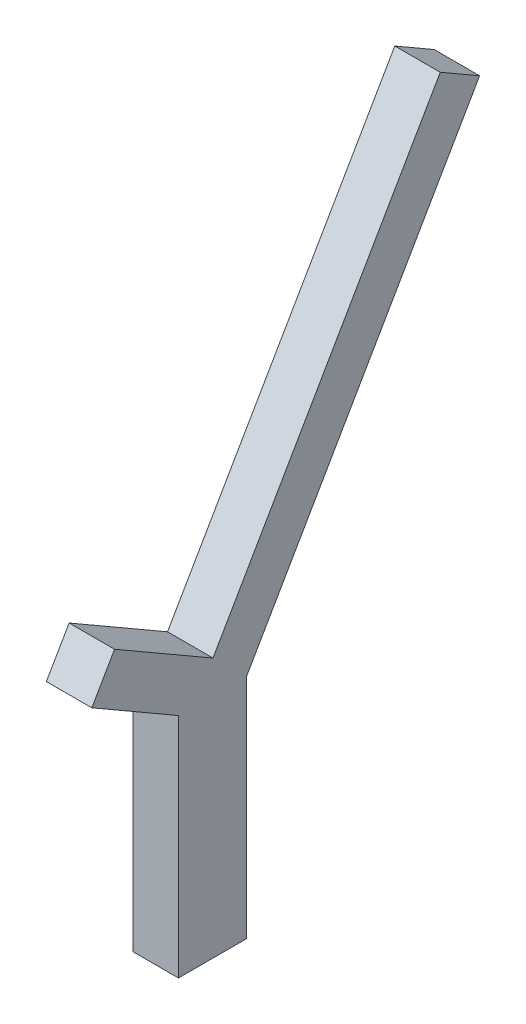
SolidWorks part; units mm, degrees
ref_plane "Front Plane" through (0, 0, 0) normal (0, 0, 1) x (1, 0, 0)
ref_plane "Top Plane" through (0, 0, 0) normal (0, 1, 0) x (1, 0, 0)
ref_plane "Right Plane" through (0, 0, 0) normal (1, 0, 0) x (0, 0, -1)
sketch "Sketch1" plane through (0, 0, 0) normal (1, 0, 0) x (0, 0, -1)
  line L0 (40.6172, 76.2768) -> (-9.3828, -10.3257)
  line L1 (-9.3828, -10.3257) -> (-31.0335, 2.1743)
  line L2 (-31.0335, 2.1743) -> (-36.0335, -6.486)
  line L3 (-36.0335, -6.486) -> (-16.9726, -17.4908)
  line L4 (-16.9726, -17.4908) -> (-16.9726, -67.4908)
  line L5 (-16.9726, -67.4908) -> (-1.9726, -67.4908)
  line L6 (-1.9726, -67.4908) -> (-1.9726, -17.4908)
  line L7 (-1.9726, -17.4908) -> (49.2774, 71.2768)
  line L8 (49.2774, 71.2768) -> (40.6172, 76.2768)
  dimension "D1" = 10
  dimension "D2" = 15
  dimension "D3" = 10
  dimension "D4" = 120
  dimension "D5" = 25
  dimension "D6" = 100
  dimension "50" = 50
extrude "Boss-Extrude1" add sketch "Sketch1" along normal blind 10
